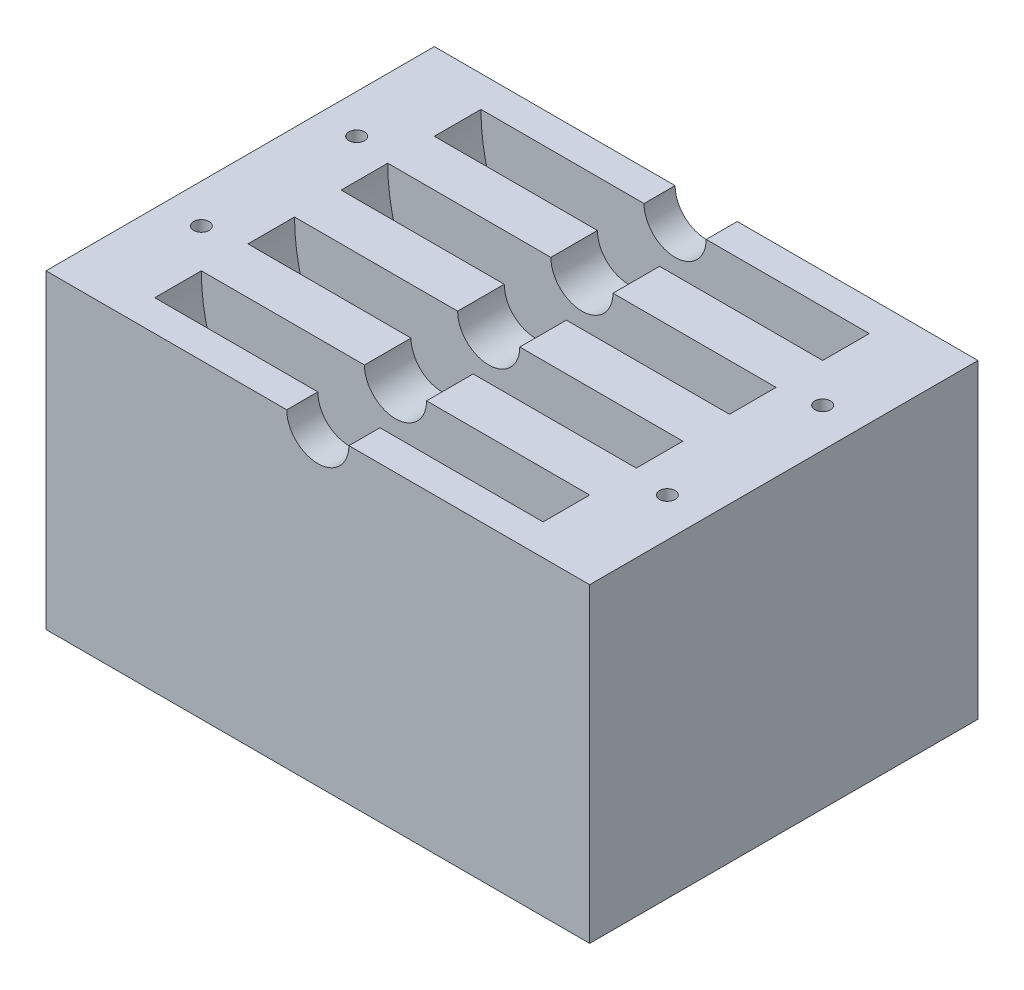
SolidWorks part; units mm, degrees
ref_plane "Front Plane" through (0, 0, 0) normal (0, 0, 1) x (1, 0, 0)
ref_plane "Top Plane" through (0, 0, 0) normal (0, 1, 0) x (1, 0, 0)
ref_plane "Right Plane" through (0, 0, 0) normal (1, 0, 0) x (0, 0, -1)
sketch "Sketch1" plane through (0, 0, 0) normal (0, 0, 1) x (1, 0, 0)
  line L0 (-152.3787, 0) -> (152.3787, 0) construction
  line L1 (0, -123.5283) -> (0, 123.5283) construction
  line L2 (-125, -94.929) -> (-125, 94.929) construction
  line L3 (125, -114.5695) -> (125, 114.5695) construction
  line L4 (125, -35.7071) -> (125, -54.0244)
  line L5 (110, -200) -> (125, -200)
  line L6 (110, -127.2308) -> (110, 127.2308) construction
  line L10 (125, 0) -> (175, 0)
  line L11 (175, 0) -> (175, -200)
  line L12 (110, -200) -> (110, -80.2722)
  line L13 (175, -200) -> (125, -200)
  line L16 (-110, -200) -> (-125, -200)
  line L17 (-175, -200) -> (-125, -200)
  line L18 (-175, 0) -> (-175, -200)
  line L19 (-125, 0) -> (-175, 0)
  line L21 (110, -59.3717) -> (110, -69.282)
  line L22 (-110, -59.3717) -> (-110, -69.282)
  line L23 (-125, -35.7071) -> (-125, -54.0244)
  line L24 (-110, -200) -> (-110, -80.2722)
  circle A0 centre (0, 0) radius 25 construction
  circle A1 centre (0, 0) radius 100 construction
  circle A2 centre (0, 0) radius 125 construction
  circle A4 centre (0, 0) radius 130 construction
  circle A5 centre (0, 0) radius 136.175 construction
  arc A6 (125, -54.0244) -> (110, -80.2722) centre (0, 0) cw
  arc A7 (125, 0) -> (110, -59.3717) centre (0, 0) cw
  arc A8 (125, -35.7071) -> (110, -69.282) centre (0, 0) cw
  arc A9 (-125, 0) -> (-110, -59.3717) centre (0, 0) ccw
  arc A10 (-125, -35.7071) -> (-110, -69.282) centre (0, 0) ccw
  arc A11 (-125, -54.0244) -> (-110, -80.2722) centre (0, 0) ccw
  point P4 (0, 0)
  point P8 (0, 0)
  point P11 (-125, 0)
  point P14 (125, 0)
  point P23 (110, 0)
  point P33 (94.6716, -183.3267)
  point P45 (125, -53.1945)
  dimension "D3" = 50
  dimension "D4" = 200
  dimension "D1" = 125
  dimension "D2" = 125
  dimension "D5" = 200
  dimension "D6" = 50
  dimension "D9" = 6.175
  dimension "D7" = 25
  dimension "D8" = 5
extrude "Boss-Extrude1" add sketch "Sketch1" along normal mid plane 210
sketch "Sketch6" plane through (0, 0, 0) normal (0, 0, 1) x (1, 0, 0)
  line L0 (-274.2667, 0) -> (274.2667, 0) construction
  line L1 (0, -153.9666) -> (0, 153.9666) construction
  line L2 (-110, -69.282) -> (-110, -59.3717)
  line L3 (-125, 0) -> (125, 0)
  line L4 (-110, -69.282) -> (110, -69.282)
  line L5 (110, -69.282) -> (110, -59.3717)
  arc A0 (-110, -59.3717) -> (-125, 0) centre (0, 0) cw
  arc A1 (-125, 0) -> (-110, -59.3717) centre (0, 0) ccw construction
  arc A2 (110, -59.3717) -> (125, 0) centre (0, 0) ccw
  point P5 (0, 0)
  point P9 (0, 0)
  point P20 (0, -69.282)
extrude "Boss-Extrude6" add sketch "Sketch6" along normal mid plane 30
sketch3d "3DSketch3"
  line L0 (-110, -59.3717, 45) -> (-110, -69.282, 45)
  line L1 (-110, -69.282, 45) -> (110, -69.282, 45)
  line L2 (0, -105.5171, 45) -> (0, 105.5171, 45) construction
  line L3 (125, 0, 15) -> (-125, 0, 15) construction
  line L4 (125, 0, 45) -> (-125, 0, 45)
  line L5 (110, -59.3717, 45) -> (110, -69.282, 45)
  arc A0 (-110, -59.3717, 45) -> (-125, 0, 45) centre (0, 0, 45) cw
  arc A1 (110, -59.3717, 45) -> (125, 0, 45) centre (0, 0, 45) ccw
  point P9 (0, 0, 45)
  point P15 (0, 0, -80)
  point P16 (0, -69.282, 45)
  point P18 (0, 0, 170)
  dimension "D1" = 45
extrude "Boss-Extrude9" add sketch "3DSketch3" along direction (0, 0, 1) on the side against the normal blind 30
sketch3d "3DSketch4"
  line L0 (110, -59.3717, -45) -> (110, -69.282, -45)
  line L1 (110, -69.282, -45) -> (-110, -69.282, -45)
  line L2 (0, -120.9329, -45) -> (0, 120.9329, -45) construction
  line L3 (125, 0, -15) -> (-125, 0, -15) construction
  line L4 (125, 0, -45) -> (-125, 0, -45)
  line L5 (-110, -59.3717, -45) -> (-110, -69.282, -45)
  arc A0 (110, -59.3717, -45) -> (125, 0, -45) centre (0, 0, -45) ccw
  arc A1 (-110, -59.3717, -45) -> (-125, 0, -45) centre (0, 0, -45) cw
  point P9 (0, 0, -45)
  point P15 (0, 0, 80)
  point P16 (0, -69.282, -45)
  point P18 (0, 0, -170)
  dimension "D1" = 45
extrude "Boss-Extrude10" add sketch "3DSketch4" along direction (0, 0, -1) on the side against the normal blind 30
sketch "Sketch7" plane through (0, 0, 105) normal (0, 0, 1) x (1, 0, 0)
  line L0 (-278.7017, 0) -> (-175, 0) construction
  line L2 (0, -136.568) -> (0, 136.568) construction
  line L3 (-175, 0) -> (-175, -200)
  line L4 (-175, -200) -> (175, -200)
  line L5 (175, -200) -> (175, 0)
  line L6 (0, 0) -> (278.7017, 0) construction
  line L7 (-175, 0) -> (175, 0)
  point P3 (0, 0)
  point P7 (0, 0)
extrude "Boss-Extrude11" add sketch "Sketch7" along normal blind 20
sketch "Sketch8" plane through (0, 0, -105) normal (0, 0, -1) x (-1, 0, 0)
  line L0 (-175, 0) -> (-175, -200)
  line L1 (-175, -200) -> (175, -200)
  line L2 (175, -200) -> (175, 0)
  line L3 (175, 0) -> (-175, 0)
extrude "Boss-Extrude12" add sketch "Sketch8" along normal blind 20
sketch "Sketch9" plane through (0, 0, 125) normal (0, 0, 1) x (1, 0, 0)
  line L0 (175, 0) -> (-175, 0) construction
  circle A0 centre (0, 0) radius 20
  dimension "D1" = 40
extrude "Cut-Extrude1" cut sketch "Sketch9" against normal blind 300
sketch "Sketch10" plane through (0, 0, 0) normal (0, 1, 0) x (1, 0, 0)
  line L0 (-321.7147, 0) -> (321.7147, 0) construction
  line L1 (0, -199.2385) -> (0, 199.2385) construction
  line L2 (150, -163.3777) -> (150, 163.3777) construction
  line L3 (175, -125) -> (175, 125) construction
  circle A0 centre (150, 50) radius 5
  circle A1 centre (150, -50) radius 5
  circle A2 centre (-150, -50) radius 5
  circle A3 centre (-150, 50) radius 5
  point P4 (0, 0)
  point P8 (0, 0)
  point P11 (150, 0)
  dimension "D2" = 10
  dimension "D3" = 50
  dimension "D1" = 25
extrude "Cut-Extrude2" cut sketch "Sketch10" against normal blind 20
